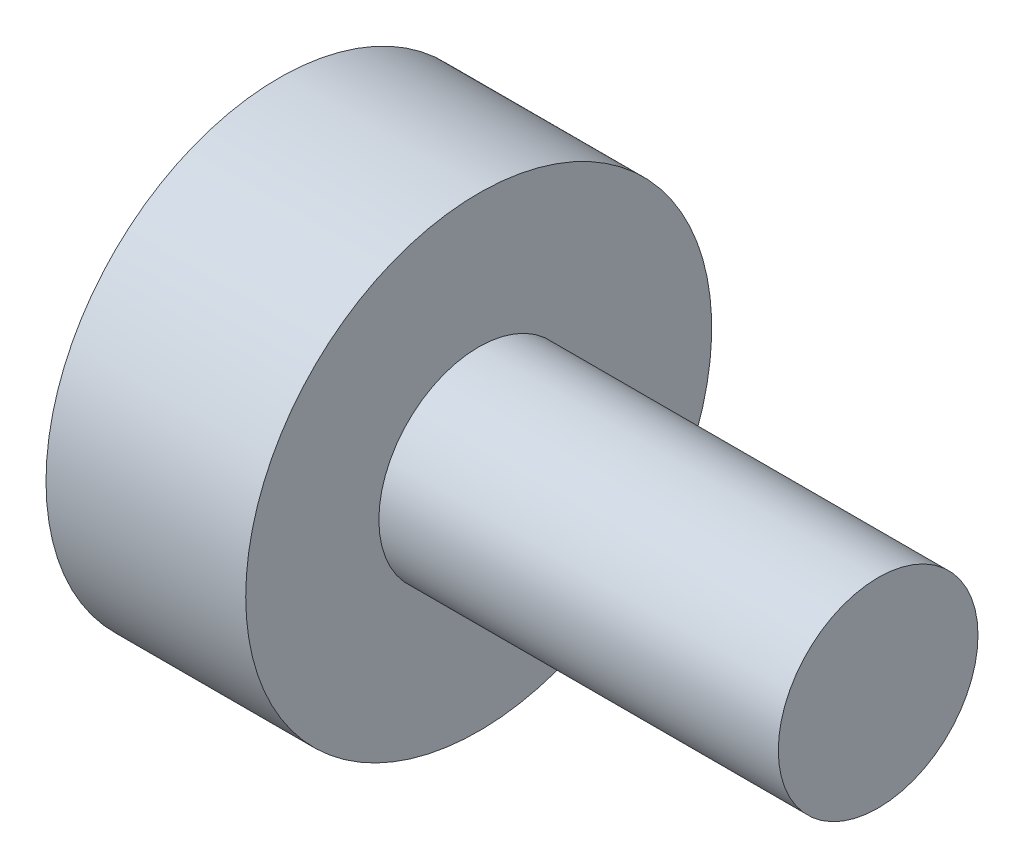
SolidWorks part; units mm, degrees
ref_plane "Спереди" through (0, 0, 0) normal (0, 0, 1) x (1, 0, 0)
ref_plane "Сверху" through (0, 0, 0) normal (0, 1, 0) x (1, 0, 0)
ref_plane "Справа" through (0, 0, 0) normal (1, 0, 0) x (0, 0, -1)
sketch "Эскиз1" plane through (0, 0, 0) normal (0, 0, 1) x (1, 0, 0)
  line L0 (0, 0) -> (100, 0)
  line L1 (0, 0) -> (0, 20)
  line L2 (0, 20) -> (10, 20)
  line L3 (10, 20) -> (10, 35)
  line L4 (10, 35) -> (40, 35)
  line L5 (40, 35) -> (40, 15)
  line L6 (40, 15) -> (100, 15)
  line L7 (100, 0) -> (100, 15)
revolve "Повернуть1" add sketch "Эскиз1" angle 360 about L0
ref_plane "Плоскость4" through (25, 0, 0) normal (1, 0, 0) x (0, 0, -1)
sketch "Эскиз2" plane through (25, 0, 0) normal (1, 0, 0) x (0, 0, -1)
  circle A0 centre (0, 0) radius 5
extrude "Вырез-Вытянуть1" cut sketch "Эскиз2" along normal blind 20
